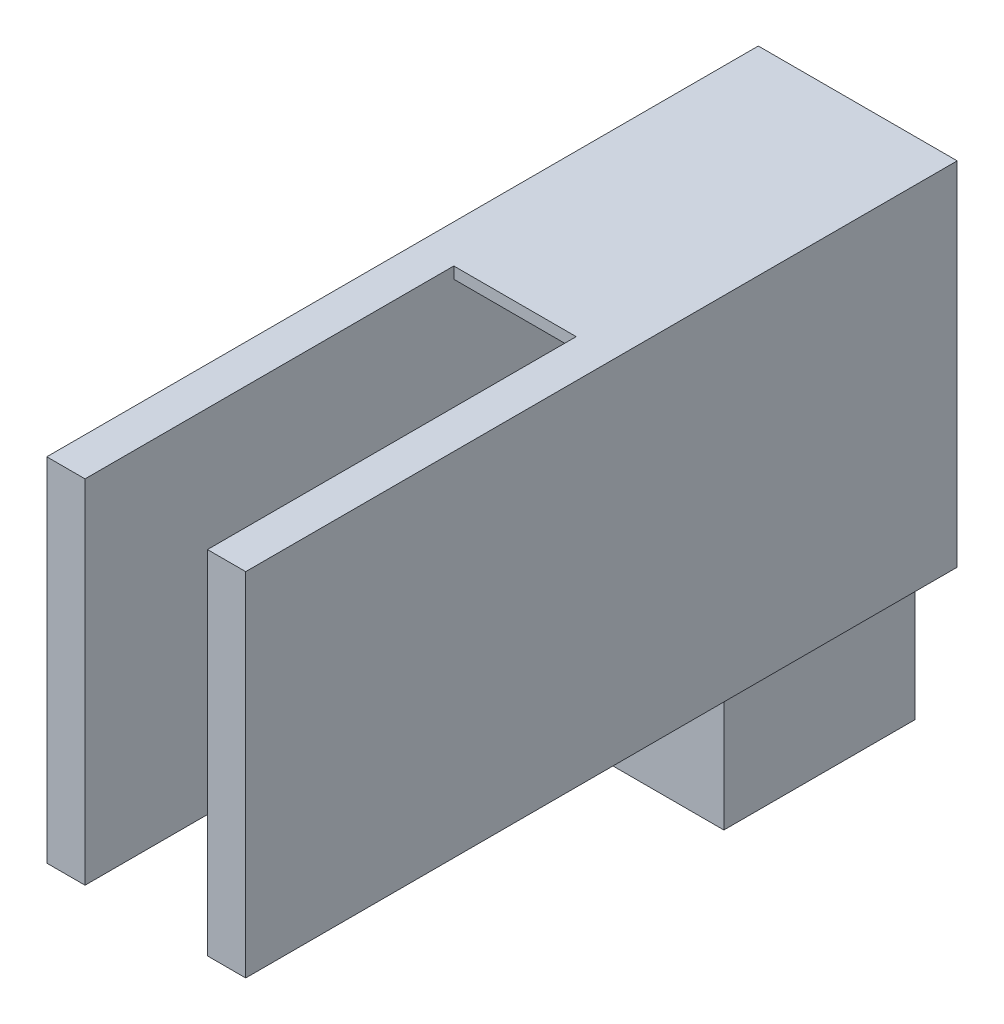
SolidWorks part; units mm, degrees
ref_plane "정면" through (0, 0, 0) normal (0, 0, 1) x (1, 0, 0)
ref_plane "윗면" through (0, 0, 0) normal (0, 1, 0) x (1, 0, 0)
ref_plane "우측면" through (0, 0, 0) normal (1, 0, 0) x (0, 0, -1)
sketch "스케치2" plane through (0, 0, 0) normal (0, 0, 1) x (1, 0, 0)
  line L1 (-13, 23) -> (13, 23)
  line L2 (-13, 23) -> (-13, -23)
  line L3 (-13, -23) -> (13, -23)
  line L4 (13, 23) -> (13, -23)
  line L5 (-13, 23) -> (13, -23) construction
  line L6 (-13, -23) -> (13, 23) construction
  point P0 (0, 0)
  dimension "D1" = 26
  dimension "D2" = 46
extrude "보스-돌출1" add sketch "스케치2" along normal blind 93
sketch "스케치3" plane through (0, 0, 0) normal (1, 0, 0) x (0, 0, -1)
  line L1 (-93, -23) -> (-20, -23)
  line L2 (-93, -23) -> (-93, 23)
  line L3 (-44.8, 21.5) -> (-20, 21.5)
  line L4 (-20, -23) -> (-20, 21.5)
  line L5 (-93, 23) -> (-44.8, 23)
  line L6 (-44.8, 23) -> (-44.8, 21.5)
  dimension "D1" = 24.8
  dimension "D2" = 20
extrude "컷-돌출1" cut sketch "스케치3" against normal mid plane 16
sketch "스케치7" plane through (0, 0, 0) normal (1, 0, 0) x (0, 0, -1)
  line L1 (-25, -23) -> (0, -23)
  line L2 (-25, -23) -> (-25, -43)
  line L3 (-25, -43) -> (0, -43)
  line L4 (0, -23) -> (0, -43)
  dimension "D1" = 25
  dimension "D2" = 20
extrude "보스-돌출2" add sketch "스케치7" along normal mid plane 15
